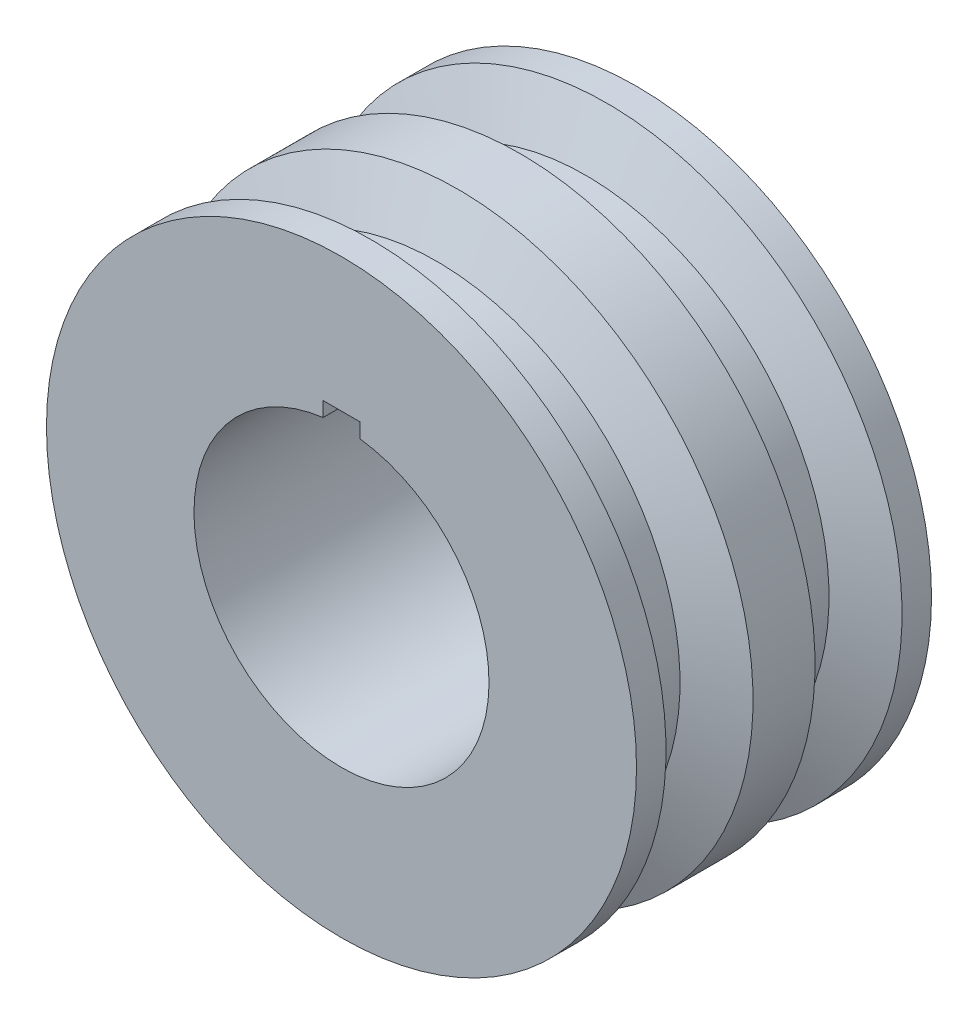
SolidWorks part; units mm, degrees
ref_plane "Płaszczyzna przednia" through (0, 0, 0) normal (0, 0, 1) x (1, 0, 0)
ref_plane "Płaszczyzna górna" through (0, 0, 0) normal (0, 1, 0) x (1, 0, 0)
ref_plane "Płaszczyzna prawa" through (0, 0, 0) normal (1, 0, 0) x (0, 0, -1)
sketch "Szkic1" plane through (0, 0, 0) normal (0, 0, 1) x (1, 0, 0)
  line L0 (0, 38.6793) -> (0, 21.8431) construction
  line L1 (-54.3187, 0) -> (55.149, 0) construction
  line L2 (-2.5, 19.8431) -> (-2.5, 21.8431)
  line L3 (-2.5, 21.8431) -> (2.5, 21.8431)
  line L4 (2.5, 21.8431) -> (2.5, 19.8431)
  line L5 (0, 20) -> (0, -49.5458) construction
  arc A0 (-2.5, 19.8431) -> (2.5, 19.8431) centre (0, 0) ccw
  circle A1 centre (0, 0) radius 40
  point P9 (0, 21.8431)
  dimension "D1" = 20
  dimension "D4" = 80
  dimension "D2" = 2
  dimension "D3" = 5
extrude "Dodanie-wyciągnięcie1" add sketch "Szkic1" along normal blind 40
sketch "Szkic3" plane through (0, 0, 0) normal (0, 1, 0) x (1, 0, 0)
  line L0 (-40, -20) -> (40, -20) construction
  line L1 (-40, 0) -> (-40, -40) construction
  line L2 (40, -40) -> (40, 0) construction
  line L3 (0, 0) -> (0, -40) construction
  line L4 (-40, -40) -> (40, -40) construction
  line L5 (40, -4) -> (33, -6.8995)
  line L6 (33, -6.8995) -> (33, -12.8995)
  line L7 (33, -12.8995) -> (40, -15.799)
  line L8 (40, -4) -> (40, -15.799)
  line L9 (40, -36) -> (40, -24.201)
  line L10 (40, -36) -> (33, -33.1005)
  line L11 (33, -33.1005) -> (33, -27.1005)
  line L12 (33, -27.1005) -> (40, -24.201)
  dimension "D1" = 45
  dimension "D2" = 4
  dimension "D3" = 6
  dimension "D4" = 7
revolve "Wycięcie-obrót1" cut sketch "Szkic3" angle 360 about L3
